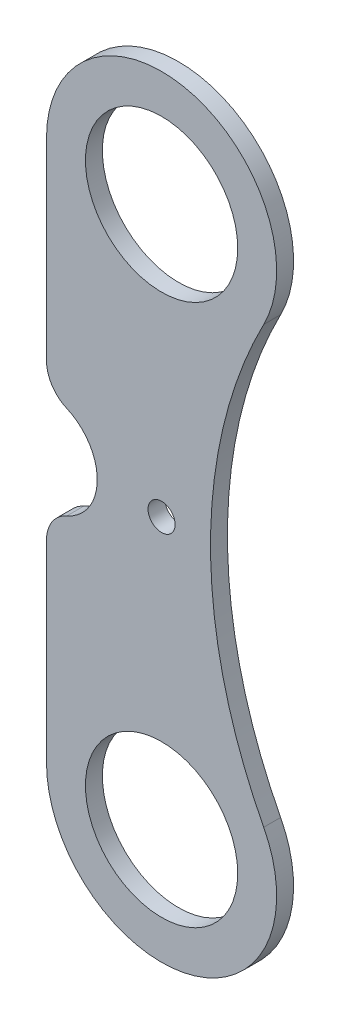
SolidWorks part; units mm, degrees
material "6061 Alloy"
ref_plane "Front Plane" through (0, 0, 0) normal (0, 0, 1) x (1, 0, 0)
ref_plane "Top Plane" through (0, 0, 0) normal (0, 1, 0) x (1, 0, 0)
ref_plane "Right Plane" through (0, 0, 0) normal (1, 0, 0) x (0, 0, -1)
sketch "Sketch1" plane through (0, 0, 0) normal (0, 0, 1) x (1, 0, 0)
  line L0 (0, 0) -> (0, -101.6) construction
  line L1 (21.59, -120.5575) -> (-21.59, -120.5575) construction
  line L2 (-8.89, 25.4) -> (8.89, 25.4)
  line L3 (-21.59, 12.7) -> (-21.59, -117.7751)
  line L5 (21.59, 12.7) -> (21.59, -117.7751)
  line L9 (-23.3829, -122.6853) -> (-33.2033, -134.3394)
  line L10 (-36.322, 25.4) -> (20.828, 25.4) construction
  line L11 (-36.322, 25.4) -> (-36.322, -203.2) construction
  line L12 (-36.322, -203.2) -> (20.828, -203.2) construction
  line L13 (20.828, 25.4) -> (20.828, -203.2) construction
  line L15 (-7.9527, -155.6168) -> (19.7971, -122.6853)
  line L16 (-32.4392, -143.2871) -> (-16.9004, -156.3809)
  circle A0 centre (0, 0) radius 38.1 construction
  circle A1 centre (0, -101.6) radius 38.1 construction
  circle A2 centre (0, 0) radius 14.2875
  circle A3 centre (0, -101.6) radius 14.2875
  arc A6 (8.89, 25.4) -> (21.59, 12.7) centre (8.89, 12.7) cw
  arc A7 (-8.89, 25.4) -> (-21.59, 12.7) centre (-8.89, 12.7) ccw
  circle A10 centre (-18.5321, -142.5501) radius 2.54
  arc A13 (-23.3829, -122.6853) -> (-21.59, -117.7751) centre (-29.21, -117.7751) ccw
  arc A14 (19.7971, -122.6853) -> (21.59, -117.7751) centre (13.97, -117.7751) ccw
  arc A15 (-16.9004, -156.3809) -> (-7.9527, -155.6168) centre (-12.8086, -151.525) ccw
  arc A16 (-33.2033, -134.3394) -> (-32.4392, -143.2871) centre (-28.3474, -138.4312) ccw
  circle A17 centre (0, -50.8) radius 2.54
  point P13 (-192.705, 39.2708)
  point P20 (21.59, 25.4)
  point P23 (-21.59, 25.4)
  point P31 (-36.322, -138.0404)
  dimension "D2" = 76.2
  dimension "D3" = 76.2
  dimension "D4" = 28.575
  dimension "D5" = 28.575
  dimension "D10" = 228.6
  dimension "D11" = 36.322
  dimension "D13" = 5.08
  dimension "D19" = 6.35
  dimension "D20" = 7.62
  dimension "D21" = 12.7
  dimension "D22" = 5.08
  dimension "D1" = 101.6
  dimension "D6" = 43.18
  dimension "D7" = 21.59
  dimension "D8" = 25.4
  dimension "D9" = 57.15
  dimension "D12" = 25.4
  dimension "D14" = 33.02
  dimension "D15" = 16.51
  dimension "D16" = 21.59
  dimension "D17" = 9.525
  dimension "D18" = 18.9575
extrude "Boss-Extrude1" add sketch "Sketch1" along normal blind 3.175
sketch "Sketch2" plane through (0, 0, 0) normal (0, 0, 1) x (1, 0, 0)
  line L0 (-21.59, -41.275) -> (-21.59, -60.325)
  line L1 (0, 0) -> (0, -101.6) construction
  line L4 (21.59, -117.7751) -> (21.59, 12.7) construction
  line L5 (-21.59, -50.8) -> (97.79, -50.8) construction
  line L6 (-21.59, 12.7) -> (-21.59, -117.7751) construction
  line L7 (0, 0) -> (-39.9512, 0) construction
  line L9 (16.51, -115.5122) -> (-17.5013, -155.8745)
  line L10 (-32.4392, -143.2871) -> (-16.9004, -156.3809) construction
  line L11 (-7.9527, -155.6168) -> (19.7971, -122.6853) construction
  line L13 (27.94, -121.6567) -> (-7.6203, -163.8572)
  line L14 (-7.6203, -163.8572) -> (-17.5013, -155.8745)
  line L15 (27.94, -121.6567) -> (27.94, 0)
  line L16 (27.94, 0) -> (21.59, 0)
  arc A1 (19.1591, -91.6472) -> (19.1591, -9.9528) centre (97.79, -50.8) cw
  arc A2 (-21.59, -60.325) -> (-21.59, -41.275) centre (-21.59, -50.8) ccw
  arc A3 (21.59, 0) -> (19.1591, -9.9528) centre (0, 0) cw
  arc A4 (21.59, -101.6) -> (19.1591, -91.6472) centre (0, -101.6) ccw
  arc A5 (21.59, -101.6) -> (16.51, -115.5122) centre (0, -101.6) cw
  dimension "D2" = 12.7
  dimension "D3" = 50.8
  dimension "D4" = 6.35
  dimension "D1" = 76.2
  dimension "D5" = 19.05
extrude "Cut-Extrude1" cut sketch "Sketch2" along normal through all contours A1 A3 L16 L15 L13 L14 L9 A5 A4 | L0 A2
sketch "Sketch3" plane through (0, 0, 3.175) normal (0, 0, 1) x (1, 0, 0)
  line L0 (-27.3514, -127.3948) -> (-36.0255, -137.6886)
  line L3 (-27.3514, -127.3948) -> (-7.5576, -144.074)
  line L4 (-23.3829, -122.6853) -> (-33.2033, -134.3394) construction
  line L5 (16.51, -115.5122) -> (-17.5013, -155.8745) construction
  line L7 (-35.4064, -144.9387) -> (-24.4031, -154.2106)
  line L8 (-23.3829, -122.6853) -> (-33.2033, -134.3394) construction
  line L9 (-7.5576, -144.074) -> (-15.4554, -153.4465)
  line L10 (-32.4392, -143.2871) -> (-17.5013, -155.8745) construction
  circle A2 centre (-18.5321, -142.5501) radius 2.54
  circle A3 centre (-18.5321, -142.5501) radius 2.54 construction
  arc A5 (-36.0255, -137.6886) -> (-35.4064, -144.9387) centre (-32.0909, -141.0041) ccw
  arc A6 (-24.4031, -154.2106) -> (-15.4554, -153.4465) centre (-20.3113, -149.3547) ccw
  dimension "D2" = 6.35
  dimension "D3" = 5.1453
  dimension "D1" = 3.175
fillet "Fillet3" radius 6.35 2 edges at (-21.59, -60.325, 1.5875) (-21.59, -41.275, 1.5875)
extrude "Boss-Extrude3" add sketch "Sketch3" against normal blind 3.175
sketch "Sketch6" plane through (0, 0, 3.175) normal (0, 0, 1) x (1, 0, 0)
  line L0 (-35.4064, -144.9387) -> (-63.6204, -121.1641)
  line L1 (-63.6204, -121.1641) -> (-51.345, -106.5965)
  line L2 (-51.345, -106.5965) -> (-27.0656, -127.0555)
  line L4 (-35.4064, -144.9387) -> (-24.4031, -154.2106) construction
  line L5 (-23.3829, -122.6853) -> (-36.0255, -137.6886) construction
  line L6 (-35.4064, -144.9387) -> (-27.0656, -127.0555)
  circle A0 centre (-52.6268, -117.9721) radius 2.54
  dimension "D4" = 5.08
  dimension "D1" = 31.75
  dimension "D2" = 9.525
  dimension "1" = 19.05
  dimension "D3" = 6.35
extrude "Boss-Extrude4" add sketch "Sketch6" against normal blind 3.175
fillet "Fillet2" radius 6.35 3 edges at (-63.6204, -121.1641, 1.5875) (-51.345, -106.5965, 1.5875) (-27.0656, -127.0555, 1.5875)
sketch "Sketch7" plane through (0, 0, 3.175) normal (0, 0, 1) x (1, 0, 0)
  line L0 (-21.59, 12.7) -> (-21.59, -36.2503) construction
  line L1 (21.59, 0) -> (21.59, 12.7) construction
  line L2 (-21.59, 0) -> (21.59, 0) construction
  line L3 (-21.59, 0) -> (-21.59, 31.75)
  line L4 (-21.59, 31.75) -> (21.59, 31.75)
  line L5 (21.59, 31.75) -> (21.59, 0)
  line L6 (8.89, 25.4) -> (-8.89, 25.4) construction
  arc A0 (-21.59, 0) -> (21.59, 0) centre (0, 0) cw
  dimension "D1" = 6.35
extrude "Cut-Extrude2" cut sketch "Sketch7" against normal through all
sketch "Sketch10" plane through (0, 0, 3.175) normal (0, 0, 1) x (1, 0, 0)
  line L0 (16.51, -115.5122) -> (-17.5013, -155.8745) construction
  line L1 (-18.1519, -155.3263) -> (-17.3615, -157.512)
  line L2 (-17.3615, -157.512) -> (-14.3757, -156.4323)
  line L3 (-14.3757, -156.4323) -> (-15.4554, -153.4465)
  line L5 (-18.1519, -155.3263) -> (-17.5013, -155.8745) construction
  circle A0 centre (-20.3113, -149.3547) radius 6.35 construction
  arc A1 (-24.4031, -154.2106) -> (-18.1519, -155.3263) centre (-20.3113, -149.3547) ccw construction
  arc A2 (-18.1519, -155.3263) -> (-15.4554, -153.4465) centre (-20.3113, -149.3547) ccw
  dimension "D1" = 3.175
  dimension "D2" = 30
extrude "Cut-Extrude3" cut sketch "Sketch10" against normal through all
sketch "Sketch12" plane through (0, 0, 3.175) normal (0, 0, 1) x (1, 0, 0)
  line L0 (-21.59, -65.3497) -> (-21.59, -117.7751) construction
  line L1 (-21.59, -101.6) -> (-72.39, -101.6)
  line L2 (-72.39, -101.6) -> (-72.39, -165.1)
  line L3 (-72.39, -165.1) -> (16.51, -165.1)
  line L4 (16.51, -165.1) -> (16.51, -115.5122)
  arc A2 (16.51, -115.5122) -> (-21.59, -101.6) centre (0, -101.6) cw
  dimension "D1" = 63.5
  dimension "D2" = 88.9
extrude "Cut-Extrude4" cut sketch "Sketch12" against normal through all
